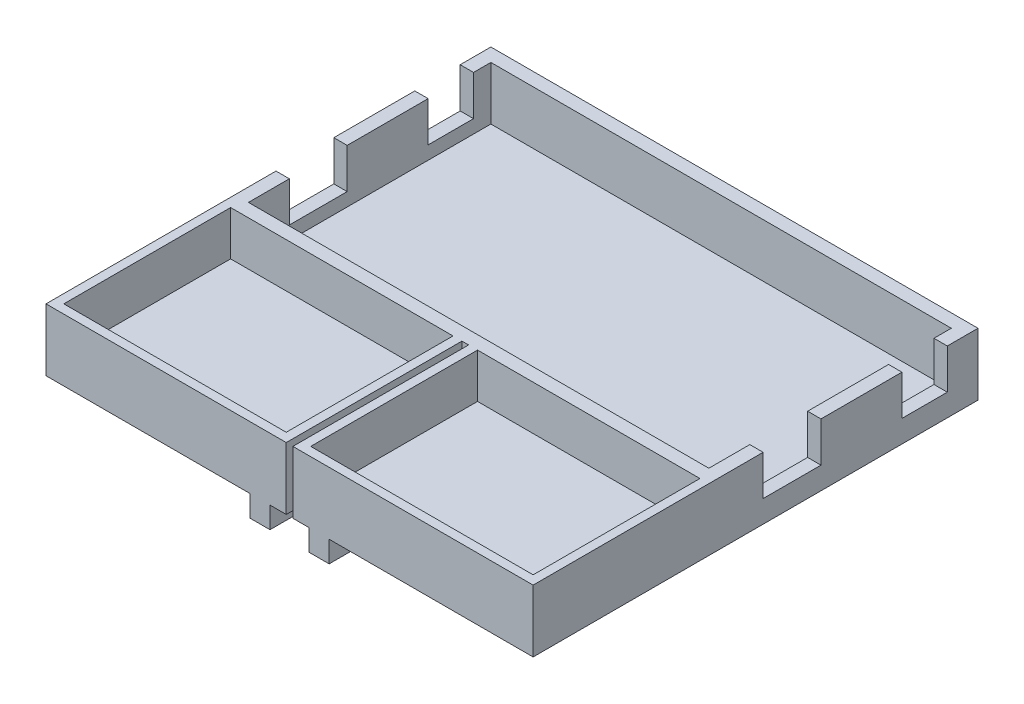
SolidWorks part; units mm, degrees
ref_plane "Front Plane" through (0, 0, 0) normal (0, 0, 1) x (1, 0, 0)
ref_plane "Top Plane" through (0, 0, 0) normal (0, 1, 0) x (1, 0, 0)
ref_plane "Right Plane" through (0, 0, 0) normal (1, 0, 0) x (0, 0, -1)
sketch "Sketch1" plane through (0, 0, 0) normal (0, 1, 0) x (1, 0, 0)
  line L1 (-54.75, -30.25) -> (54.75, -30.25)
  line L2 (-54.75, -30.25) -> (-54.75, 30.25)
  line L3 (-54.75, 30.25) -> (54.75, 30.25)
  line L4 (54.75, -30.25) -> (54.75, 30.25)
  line L5 (-54.75, -30.25) -> (54.75, 30.25) construction
  line L6 (-54.75, 30.25) -> (54.75, -30.25) construction
  point P0 (0, 0)
  dimension "D1" = 109.5
  dimension "D2" = 60.5
extrude "Boss-Extrude1" add sketch "Sketch1" along normal blind 14
sketch "Sketch2" plane through (0, 14, 0) normal (0, 1, 0) x (1, 0, 0)
  line L5 (-51.75, 27.25) -> (51.75, 27.25)
  line L6 (-51.75, 27.25) -> (-51.75, -27.25)
  line L7 (-51.75, -27.25) -> (51.75, -27.25)
  line L8 (51.75, 27.25) -> (51.75, -27.25)
  line L9 (-51.75, 27.25) -> (51.75, -27.25) construction
  line L10 (-51.75, -27.25) -> (51.75, 27.25) construction
  point P0 (0, 0)
  dimension "D1" = 103.5
  dimension "60" = 54.5
extrude "Cut-Extrude1" cut sketch "Sketch2" against normal blind 12
sketch "Sketch4" plane through (54.75, 0, 0) normal (1, 0, 0) x (0, 0, -1)
  line L0 (30.25, 5) -> (27.25, 5) construction
  line L1 (-30.25, 14) -> (-30.25, 0) construction
  line L2 (-18.05, 14) -> (-18.05, 5)
  line L7 (-30.25, 14) -> (30.25, 14) construction
  line L8 (-18.05, 5) -> (-5.05, 5)
  line L9 (-18.05, 14) -> (-5.05, 14)
  line L10 (-5.05, 14) -> (-5.05, 5)
  line L13 (-5.05, 5) -> (13.15, 5) construction
  line L14 (23.35, 14) -> (13.15, 14)
  line L15 (23.35, 14) -> (23.35, 5)
  line L16 (23.35, 5) -> (13.15, 5)
  line L17 (13.15, 14) -> (13.15, 5)
  line L21 (-30.25, 5) -> (-27.25, 5) construction
  line L22 (-27.25, 5) -> (-18.05, 5) construction
  line L23 (30.25, 14) -> (30.25, 0) construction
  line L24 (27.25, 5) -> (23.35, 5) construction
  dimension "D1" = 13
  dimension "D2" = 9
  dimension "D3" = 10.2
  dimension "D4" = 3
  dimension "D5" = 3
  dimension "D6" = 18.2
  dimension "D7" = 9.2
  dimension "D8" = 3.9
extrude "Cut-Extrude2" cut sketch "Sketch4" against normal through all
sketch "Sketch5" plane through (0, 0, 0) normal (0, -1, 0) x (1, 0, 0)
  line L0 (4.45, 0) -> (-4.45, 0) construction
  line L2 (-4.4, -30.25) -> (-4.4, 69.75)
  line L3 (-4.4, -30.25) -> (-8.9, -30.25)
  line L4 (-8.9, -30.25) -> (-8.9, 69.75)
  line L5 (-4.4, 69.75) -> (-8.9, 69.75)
  line L8 (54.75, -30.25) -> (-54.75, -30.25) construction
  point P4 (0, 0)
  dimension "D1" = 4.5
  dimension "D2" = 8.9
  dimension "D3" = 100
extrude "Boss-Extrude3" add sketch "Sketch5" along normal blind 4.8
mirror "Mirror1" about plane through (0, 0, 0) normal (1, 0, 0) of "Boss-Extrude3"
sketch "Sketch6" plane through (0, 0, 0) normal (0, 1, 0) x (1, 0, 0)
  line L1 (-54.75, -30.25) -> (54.75, -30.25) construction
  line L5 (54.75, -30.25) -> (54.75, -18.05) construction
  line L7 (0.75, -30.25) -> (0.75, -69.75)
  line L8 (0.75, -69.75) -> (54.75, -69.75)
  line L9 (54.75, -30.25) -> (54.75, -69.75)
  line L10 (-54.75, -30.25) -> (-52.75, -30.25)
  line L20 (0, -7.7) -> (0, 7.7) construction
  line L21 (-54.75, -30.25) -> (-54.75, -69.75)
  line L22 (-0.75, -69.75) -> (-54.75, -69.75)
  line L23 (-0.75, -30.25) -> (-0.75, -69.75)
  line L26 (-52.75, -30.25) -> (-2.75, -30.25)
  line L27 (-52.75, -30.25) -> (-52.75, -67.75)
  line L28 (-52.75, -67.75) -> (-2.75, -67.75)
  line L29 (-2.75, -67.75) -> (-2.75, -30.25)
  line L30 (-0.75, -30.25) -> (-2.75, -30.25)
  line L31 (52.75, -67.75) -> (2.75, -67.75)
  line L32 (2.75, -67.75) -> (2.75, -30.25)
  line L33 (52.75, -30.25) -> (2.75, -30.25)
  line L34 (52.75, -30.25) -> (52.75, -67.75)
  line L35 (0.75, -30.25) -> (2.75, -30.25)
  line L36 (54.75, -30.25) -> (52.75, -30.25)
  point P5 (27.6803, -30.114)
  point P20 (-27.75, -30.25)
  point P26 (-27.75, -69.75)
  dimension "D1" = 50
  dimension "D2" = 37.5
  dimension "D3" = 54
  dimension "D4" = 39.5
extrude "Boss-Extrude7" add sketch "Sketch6" along normal up to surface (14 mm away) contours L23 L30 L29 L28 L27 L10 L21 L22 | L9 L36 L34 L31 L32 L35 L7 L8 up to face at (0, 14, 23.4)
sketch "Sketch9" plane through (0, 0, 0) normal (0, 1, 0) x (1, 0, 0)
  line L0 (-52.75, -30.25) -> (-2.75, -30.25)
  line L2 (-52.75, -30.25) -> (-52.75, -67.75)
  line L4 (52.75, -30.25) -> (52.75, -67.75)
  line L5 (-2.75, -30.25) -> (-2.75, -67.75)
  line L6 (-2.75, -67.75) -> (-52.75, -67.75)
  line L7 (2.75, -30.25) -> (52.75, -30.25)
  line L8 (2.75, -30.25) -> (2.75, -67.75)
  line L9 (2.75, -67.75) -> (52.75, -67.75)
extrude "Boss-Extrude8" add sketch "Sketch9" along normal blind 4
